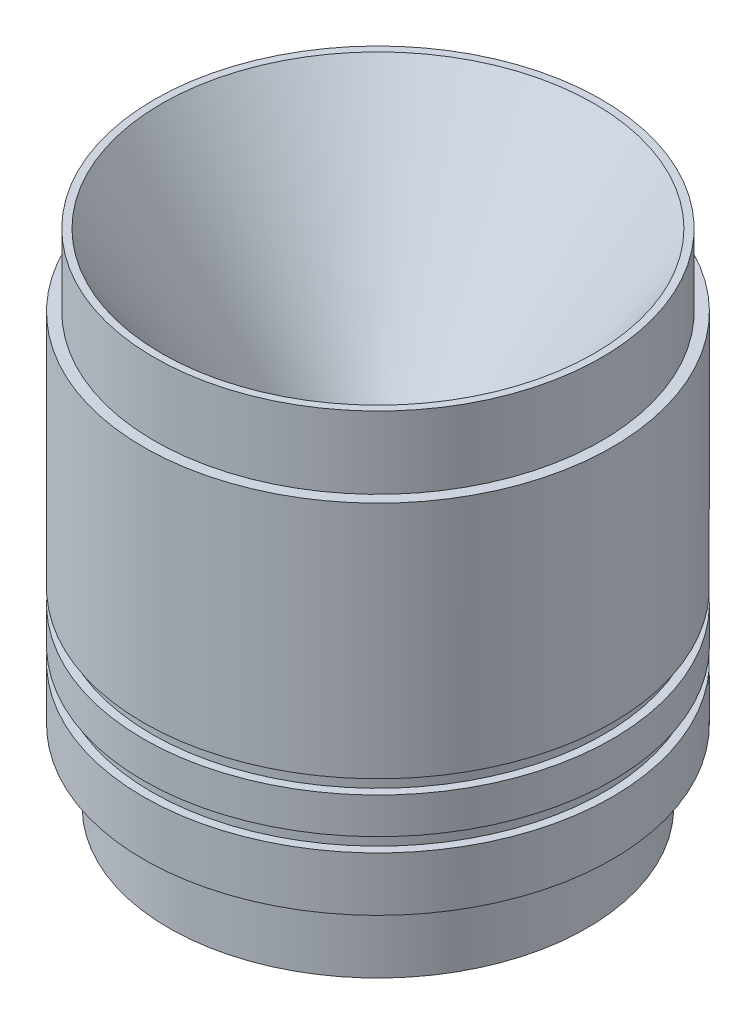
SolidWorks part; units mm, degrees
material "C (Grafit)"
ref_plane "Płaszczyzna przednia" through (0, 0, 0) normal (0, 0, 1) x (1, 0, 0)
ref_plane "Płaszczyzna górna" through (0, 0, 0) normal (0, 1, 0) x (1, 0, 0)
ref_plane "Płaszczyzna prawa" through (0, 0, 0) normal (1, 0, 0) x (0, 0, -1)
sketch "Szkic1" plane through (0, 0, 0) normal (0, 0, 1) x (1, 0, 0)
  line L0 (60, 64.359) -> (18.4364, 5)
  line L1 (18.4364, 5) -> (18.4364, -5)
  line L2 (18.4364, -5) -> (38.4364, -79.641)
  line L5 (58, -54.641) -> (65, -54.641)
  line L6 (65, -54.641) -> (65, 44.359)
  line L7 (65, 44.359) -> (62, 44.359)
  line L8 (62, 44.359) -> (62, 64.359)
  line L9 (62, 64.359) -> (60, 64.359)
  line L10 (0, 60.8246) -> (0, -87.019) construction
  line L15 (38.4364, -79.641) -> (48, -79.641)
  line L16 (48, -79.641) -> (48, -74.641)
  line L17 (48, -74.641) -> (58, -74.641)
  line L18 (58, -74.641) -> (58, -54.641)
  point P14 (18.4364, 0)
  dimension "D2" = 65
  dimension "D3" = 144
  dimension "D4" = 5
  dimension "D5" = 20
  dimension "D6" = 3
  dimension "D7" = 5
  dimension "D8" = 35
  dimension "D9" = 15
  dimension "D10" = 10
  dimension "D11" = 7
  dimension "D12" = 10
  dimension "D13" = 25
revolve "Obrót1" add sketch "Szkic1" angle 360 about L10
sketch "Szkic2" plane through (0, 0, 0) normal (0, 0, 1) x (1, 0, 0)
  line L0 (65, -39.641) -> (62.7, -39.641)
  line L1 (65, -54.641) -> (65, 44.359) construction
  line L2 (62.7, -39.641) -> (62.7, -35.741)
  line L3 (62.7, -35.741) -> (65, -35.741)
  line L4 (65, -25.741) -> (62.7, -25.741)
  line L5 (62.7, -25.741) -> (62.7, -21.841)
  line L6 (62.7, -21.841) -> (65, -21.841)
  line L7 (65, -21.841) -> (65, -25.741)
  line L8 (65, -35.741) -> (65, -39.641)
  line L10 (0, 85.8746) -> (0, -138.4714) construction
  line L11 (-48, -79.641) -> (48, -79.641) construction
  dimension "D1" = 3.9
  dimension "D2" = 3.9
  dimension "D3" = 2.3
  dimension "D4" = 2.3
  dimension "D5" = 40
  dimension "D6" = 10
revolve "Wycięcie-obrót1" cut sketch "Szkic2" angle 360 about L10
